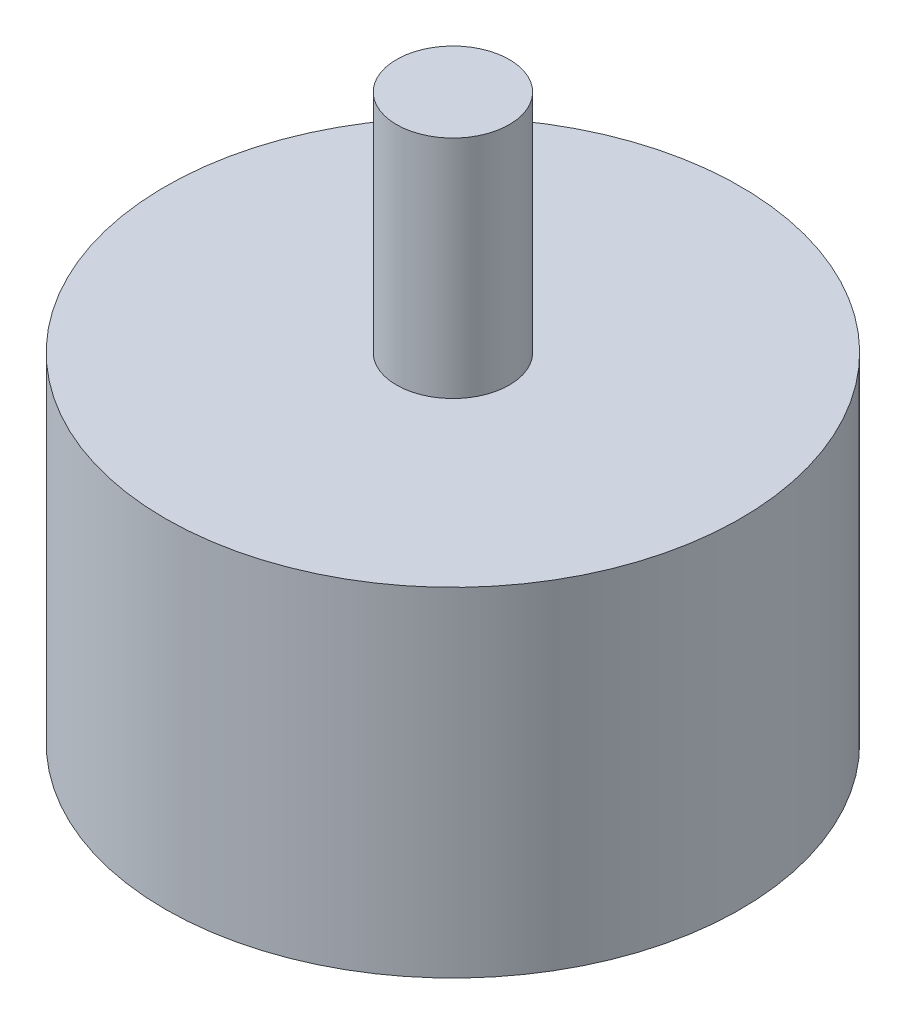
SolidWorks part; units mm, degrees
material "AISI 1020"
ref_plane "Alzado" through (0, 0, 0) normal (0, 0, 1) x (1, 0, 0)
ref_plane "Planta" through (0, 0, 0) normal (0, 1, 0) x (1, 0, 0)
ref_plane "Vista lateral" through (0, 0, 0) normal (1, 0, 0) x (0, 0, -1)
sketch "Croquis1" plane through (0, 0, 0) normal (0, 1, 0) x (1, 0, 0)
  circle A0 centre (0, 0) radius 12.75
  dimension "D1" = 25.5
extrude "Saliente-Extruir1" add sketch "Croquis1" along normal blind 15
sketch "Croquis2" plane through (0, 15, 0) normal (0, 1, 0) x (1, 0, 0)
  circle A0 centre (0, 0) radius 2.5
  dimension "D1" = 5
extrude "Saliente-Extruir2" add sketch "Croquis2" along normal blind 10
